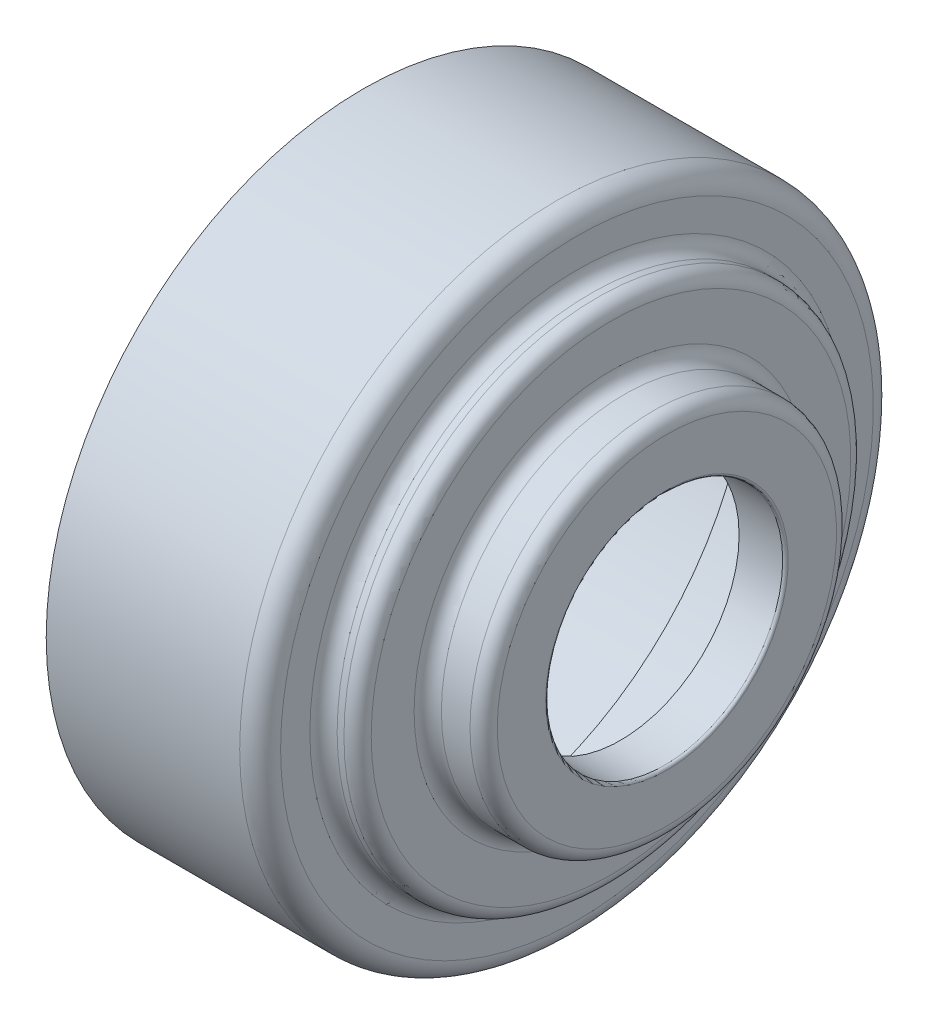
SolidWorks part; units mm, degrees
ref_plane "前视基准面" through (0, 0, 0) normal (0, 0, 1) x (1, 0, 0)
ref_plane "上视基准面" through (0, 0, 0) normal (0, 1, 0) x (1, 0, 0)
ref_plane "右视基准面" through (0, 0, 0) normal (1, 0, 0) x (0, 0, -1)
sketch "草图2" plane through (0, 0, 0) normal (0, 0, 1) x (1, 0, 0)
  line L0 (-36.9366, 0) -> (44.5849, 0) construction
  line L1 (0, 36.0368) -> (0, -37.1166) construction
  line L2 (-14.5, 22) -> (-7.5, 22)
  line L3 (-7.5, 22) -> (-7.5, 21.4)
  line L4 (-7.5, 21.4) -> (0, 21.4)
  line L5 (0, 21.4) -> (0, 17.4)
  line L6 (0, 17.4) -> (2.5, 17.4)
  line L7 (2.5, 17.4) -> (2.5, 12.25)
  line L8 (2.5, 12.25) -> (6.6, 12.25)
  line L9 (6.6, 12.25) -> (6.6, 9.4)
  line L10 (6.6, 9.4) -> (4.4, 9.4)
  line L11 (4.4, 9.4) -> (4.4, 8.7)
  line L12 (4.4, 8.7) -> (7.8, 8.7)
  line L13 (-14.5, 22) -> (-14.5, 23.25)
  line L14 (-14.5, 23.25) -> (1.2, 23.25)
  line L15 (1.2, 23.25) -> (1.2, 18.6)
  line L16 (1.2, 18.6) -> (3.7, 18.6)
  line L17 (3.7, 18.6) -> (3.7, 13.45)
  line L18 (3.7, 13.45) -> (7.8, 13.45)
  line L19 (7.8, 13.45) -> (7.8, 8.7)
  dimension "D1" = 44
  dimension "D2" = 0.6
  dimension "D3" = 7
  dimension "D4" = 7.5
  dimension "D5" = 34.8
  dimension "D6" = 2.5
  dimension "D7" = 18.8
  dimension "D8" = 0.7
  dimension "D9" = 4.4
  dimension "D10" = 2.2
  dimension "D11" = 24.5
  dimension "D12" = 1.85
  dimension "D13" = 46.5
  dimension "D14" = 1.2
  dimension "D15" = 1.2
  dimension "D16" = 1.2
  dimension "D17" = 1.2
  dimension "D18" = 1.2
revolve "旋转1" add sketch "草图2" angle 360 about L0
fillet "圆角1" radius 0.2 5 edges at (0, 0, 17.4) (0, 0, 21.4) (7.8, 0, 8.7) (2.5, 0, 17.4) (6.6, 0, 12.25)
fillet "圆角2" radius 1 4 edges at (3.7, 0, 13.45) (1.2, 0, 18.6) (3.7, 0, 18.6) (7.8, 0, 13.45)
fillet "圆角3" radius 1.5 2 edges at (1.2, 0, 23.25) (2.5, 0, 12.25)
